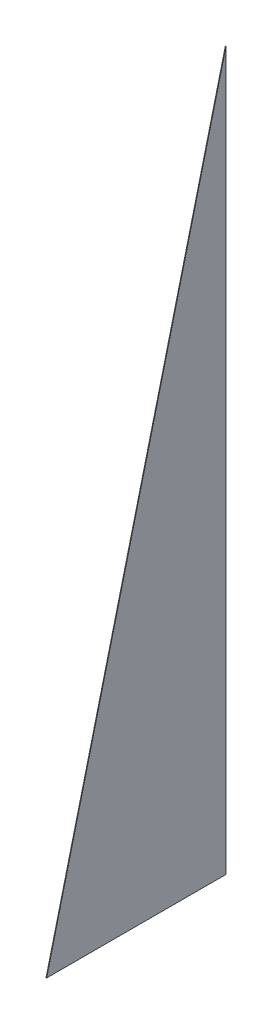
SolidWorks part; units mm, degrees
ref_plane "Front Plane" through (0, 0, 0) normal (0, 0, 1) x (1, 0, 0)
ref_plane "Top Plane" through (0, 0, 0) normal (0, 1, 0) x (1, 0, 0)
ref_plane "Right Plane" through (0, 0, 0) normal (1, 0, 0) x (0, 0, -1)
sketch "Sketch1" plane through (0, 0, 0) normal (1, 0, 0) x (0, 0, -1)
  line L0 (0, 0) -> (0, 1200)
  line L1 (0, 1200) -> (-300, 0)
  line L2 (-300, 0) -> (0, 0)
  dimension "D1" = 1200
  dimension "D2" = 300
extrude "Boss-Extrude1" add sketch "Sketch1" along normal blind 1
